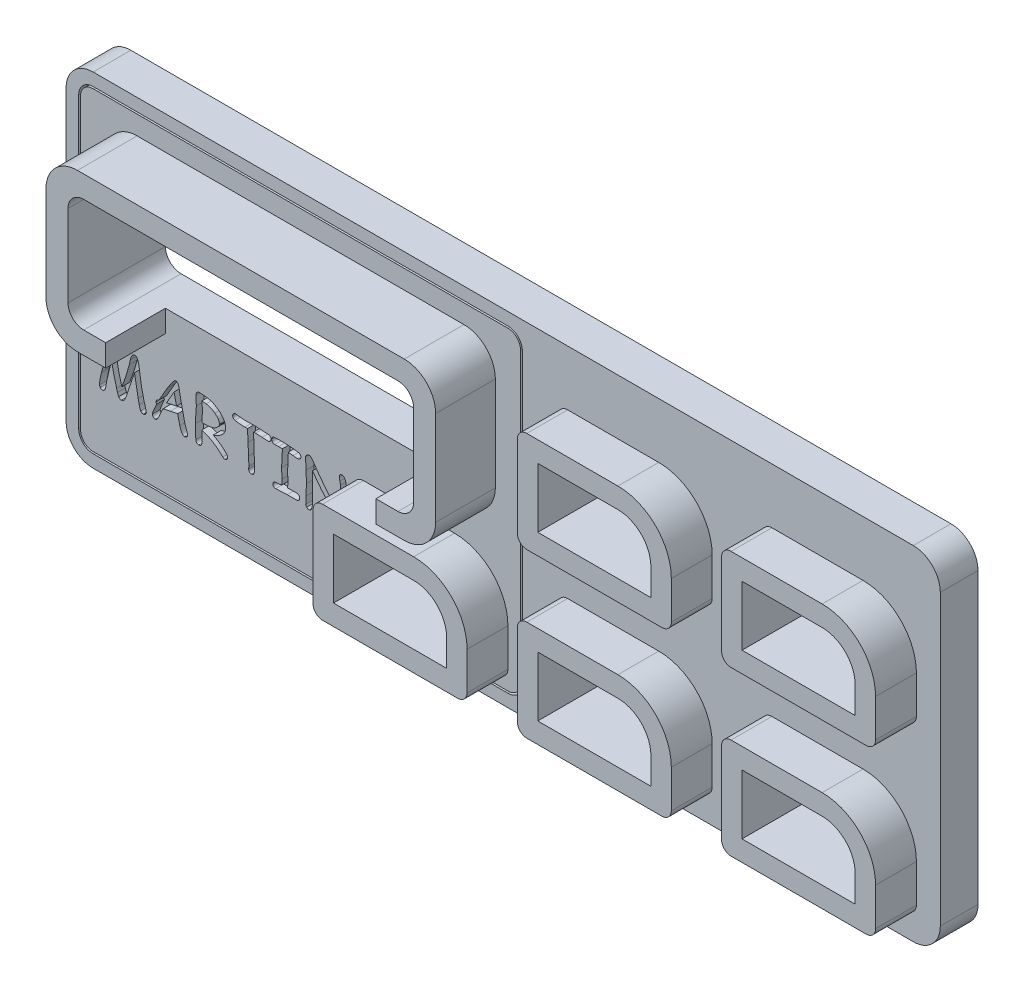
SolidWorks part; units mm, degrees
ref_plane "Plan de face" through (0, 0, 0) normal (0, 0, 1) x (1, 0, 0)
ref_plane "Plan de dessus" through (0, 0, 0) normal (0, 1, 0) x (1, 0, 0)
ref_plane "Plan de droite" through (0, 0, 0) normal (1, 0, 0) x (0, 0, -1)
sketch "Esquisse1" plane through (0, 0, 0) normal (0, 0, 1) x (1, 0, 0)
  line L1 (2, 0) -> (68, 0)
  line L2 (0, 2) -> (0, 48)
  line L3 (2, 50) -> (68, 50)
  line L4 (70, 2) -> (70, 48)
  arc A0 (68, 0) -> (70, 2) centre (68, 2) ccw
  arc A1 (0, 48) -> (2, 50) centre (2, 48) cw
  arc A2 (68, 50) -> (70, 48) centre (68, 48) cw
  arc A3 (2, 0) -> (0, 2) centre (2, 2) cw
  point P7 (70, 0)
  point P12 (70, 50)
  point P15 (0, 0)
  dimension "D3" = 2
  dimension "D1" = 70
  dimension "D2" = 50
extrude "Boss.-Extru.1" add sketch "Esquisse1" along normal blind 6
sketch "Esquisse2" plane through (0, 0, 6) normal (0, 0, 1) x (1, 0, 0)
  line L0 (35, 50) -> (35, 0) construction
  line L1 (9, 47) -> (61, 47)
  line L2 (4, 42) -> (4, 27)
  line L3 (9, 22) -> (13.5, 22)
  line L4 (66, 42) -> (66, 27)
  line L5 (68, 50) -> (2, 50) construction
  line L6 (2, 0) -> (68, 0) construction
  line L8 (7.5, 41) -> (7.5, 28)
  line L13 (10, 25.5) -> (13.5, 25.5)
  line L14 (62.5, 41) -> (62.5, 28)
  line L15 (10, 43.5) -> (60, 43.5)
  line L16 (13.5, 25.5) -> (13.5, 22)
  line L19 (56.5, 25.5) -> (56.5, 22)
  line L24 (56.5, 22) -> (61, 22)
  line L25 (56.5, 25.5) -> (60, 25.5)
  arc A0 (61, 47) -> (66, 42) centre (61, 42) cw
  arc A1 (4, 27) -> (9, 22) centre (9, 27) ccw
  arc A2 (61, 22) -> (66, 27) centre (61, 27) ccw
  arc A3 (9, 47) -> (4, 42) centre (9, 42) ccw
  arc A4 (7.5, 28) -> (10, 25.5) centre (10, 28) ccw
  arc A5 (60, 25.5) -> (62.5, 28) centre (60, 28) ccw
  arc A6 (60, 43.5) -> (62.5, 41) centre (60, 41) cw
  arc A7 (10, 43.5) -> (7.5, 41) centre (10, 41) ccw
  point P12 (66, 47)
  point P15 (4, 22)
  point P18 (66, 22)
  dimension "D4" = 5
  dimension "D6" = 3.5
  dimension "D9" = 2.5
  dimension "D1" = 62
  dimension "D2" = 25
  dimension "D3" = 3
  dimension "D5" = 3.5
  dimension "D7" = 3.5
  dimension "D8" = 3.5
  dimension "D10" = 43
extrude "Boss.-Extru.2" add sketch "Esquisse2" along normal blind 9.5
sketch "Esquisse4" plane through (0, 0, 6) normal (0, 0, 1) x (1, 0, 0)
  line L0 (2, 0) -> (68, 0) construction
  line L1 (45, 1.5) -> (66.5, 1.5)
  line L2 (43.5, 3) -> (43.5, 16)
  line L3 (45, 17.5) -> (59.5, 17.5)
  line L4 (68, 3) -> (68, 9)
  line L5 (70, 2) -> (70, 48) construction
  line L6 (46.75, 4.75) -> (46.75, 14.25)
  line L7 (46.75, 14.25) -> (59.5, 14.25)
  line L8 (64.75, 4.75) -> (64.75, 9)
  line L9 (46.75, 4.75) -> (64.75, 4.75)
  arc A0 (43.5, 16) -> (45, 17.5) centre (45, 16) cw
  arc A1 (45, 1.5) -> (43.5, 3) centre (45, 3) cw
  arc A2 (66.5, 1.5) -> (68, 3) centre (66.5, 3) ccw
  arc A3 (59.5, 17.5) -> (68, 9) centre (59.5, 9) cw
  arc A4 (46.75, 14.25) -> (46.75, 14.25) centre (46.75, 14.25) cw
  arc A5 (59.5, 14.25) -> (64.75, 9) centre (59.5, 9) cw
  arc A6 (64.75, 4.75) -> (64.75, 4.75) centre (64.75, 4.75) ccw
  arc A7 (46.75, 4.75) -> (46.75, 4.75) centre (46.75, 4.75) cw
  point P10 (43.5, 17.5)
  point P13 (43.5, 1.5)
  point P18 (68, 17.5)
  dimension "D5" = 1.5
  dimension "D6" = 8.5
  dimension "D1" = 1.5
  dimension "D2" = 2
  dimension "D3" = 24.5
  dimension "D4" = 16
  dimension "D7" = 3.25
extrude "Boss.-Extru.3" add sketch "Esquisse4" along normal blind 6.5
sketch "Esquisse5" plane through (0, 0, 6) normal (0, 0, 1) x (1, 0, 0)
  line L0 (60, 25.5) -> (56.5, 25.5) construction
  line L1 (62.5, 41) -> (62.5, 28) construction
  line L2 (10, 43.5) -> (60, 43.5) construction
  line L3 (7.5, 28) -> (7.5, 41) construction
  line L4 (46.75, 4.75) -> (64.75, 4.75)
  line L5 (64.75, 4.75) -> (64.75, 9)
  line L6 (59.5, 14.25) -> (46.75, 14.25)
  line L7 (46.75, 14.25) -> (46.75, 4.75)
  line L8 (46.75, 4.75) -> (64.75, 4.75)
  line L9 (64.75, 4.75) -> (64.75, 9)
  line L10 (59.5, 14.25) -> (46.75, 14.25)
  line L11 (46.75, 14.25) -> (46.75, 4.75)
  line L12 (60, 25.5) -> (10, 25.5)
  line L13 (62.5, 41) -> (62.5, 28)
  line L14 (10, 43.5) -> (60, 43.5)
  line L15 (7.5, 28) -> (7.5, 41)
  arc A0 (60, 25.5) -> (62.5, 28) centre (60, 28) ccw construction
  arc A1 (64.75, 9) -> (59.5, 14.25) centre (59.5, 9) ccw
  arc A2 (64.75, 9) -> (59.5, 14.25) centre (59.5, 9) ccw
  arc A3 (62.5, 41) -> (60, 43.5) centre (60, 41) ccw construction
  arc A4 (10, 43.5) -> (7.5, 41) centre (10, 41) ccw construction
  arc A5 (7.5, 28) -> (10, 25.5) centre (10, 28) ccw construction
  arc A6 (60, 25.5) -> (62.5, 28) centre (60, 28) ccw
  arc A7 (62.5, 41) -> (60, 43.5) centre (60, 41) ccw
  arc A8 (10, 43.5) -> (7.5, 41) centre (10, 41) ccw
  arc A9 (7.5, 28) -> (10, 25.5) centre (10, 28) ccw
  dimension "D1" = 0
extrude "Enlèv. mat.-Extru.1" cut sketch "Esquisse5" against normal through all
sketch "Esquisse6" plane through (0, 0, 6) normal (0, 0, 1) x (1, 0, 0)
  line L0 (2.5, 9.5) -> (43.5, 9.5) construction
  line L2 (2, 0) -> (68, 0) construction
  line L3 (0, 48) -> (0, 2) construction
  line L4 (43.5, 16) -> (43.5, 3) construction
  text T0 "MARTIN" font "Comic Sans MS" height 7
  dimension "D1" = 9.5
  dimension "D2" = 2.5
extrude "Enlèv. mat.-Extru.2" cut sketch "Esquisse6" against normal blind 1.25
sketch "Esquisse7" plane through (0, 0, 0) normal (0, 0, 1) x (1, 0, 0)
  line L0 (79.25, 4.75) -> (97.25, 4.75)
  line L4 (97.25, 4.75) -> (97.25, 9)
  line L5 (92, 14.25) -> (79.25, 14.25)
  line L6 (79.25, 14.25) -> (79.25, 4.75)
  line L7 (76, 16) -> (76, 3)
  line L13 (2, 52.3) -> (132.5, 52.3) construction
  line L14 (-2.3, 48) -> (-2.3, 2) construction
  line L15 (2, -2.3) -> (132.5, -2.3) construction
  line L16 (70.3, 2) -> (70.3, 48)
  line L17 (68, 50.3) -> (2, 50.3)
  line L18 (-0.3, 48) -> (-0.3, 2)
  line L19 (2, -0.3) -> (68, -0.3)
  line L20 (70.3, 2) -> (70.3, 48) construction
  line L21 (68, 50.3) -> (2, 50.3) construction
  line L22 (-0.3, 48) -> (-0.3, 2) construction
  line L23 (2, -0.3) -> (68, -0.3) construction
  line L24 (136.8, 48) -> (136.8, 2) construction
  line L25 (77.5, 1.5) -> (99, 1.5)
  line L26 (100.5, 3) -> (100.5, 9)
  line L27 (92, 17.5) -> (77.5, 17.5)
  line L28 (46.75, 4.75) -> (64.75, 4.75)
  line L29 (46.75, 14.25) -> (46.75, 4.75)
  line L30 (59.5, 14.25) -> (46.75, 14.25)
  line L31 (64.75, 4.75) -> (64.75, 9)
  line L32 (46.75, 4.75) -> (64.75, 4.75) construction
  line L33 (46.75, 14.25) -> (46.75, 4.75) construction
  line L34 (59.5, 14.25) -> (46.75, 14.25) construction
  line L35 (64.75, 4.75) -> (64.75, 9) construction
  line L36 (43.5, 16) -> (43.5, 3)
  line L37 (45, 1.5) -> (66.5, 1.5)
  line L38 (68, 3) -> (68, 9)
  line L39 (59.5, 17.5) -> (45, 17.5)
  line L40 (43.5, 16) -> (43.5, 3) construction
  line L41 (45, 1.5) -> (66.5, 1.5) construction
  line L42 (68, 3) -> (68, 9) construction
  line L43 (59.5, 17.5) -> (45, 17.5) construction
  line L44 (111.75, 4.75) -> (129.75, 4.75)
  line L45 (129.75, 4.75) -> (129.75, 9)
  line L46 (124.5, 14.25) -> (111.75, 14.25)
  line L47 (111.75, 14.25) -> (111.75, 4.75)
  line L48 (108.5, 16) -> (108.5, 3)
  line L49 (110, 1.5) -> (131.5, 1.5)
  line L50 (133, 3) -> (133, 9)
  line L51 (124.5, 17.5) -> (110, 17.5)
  line L52 (79.25, 30.75) -> (97.25, 30.75)
  line L53 (97.25, 30.75) -> (97.25, 35)
  line L54 (92, 40.25) -> (79.25, 40.25)
  line L55 (79.25, 40.25) -> (79.25, 30.75)
  line L56 (76, 42) -> (76, 29)
  line L57 (77.5, 27.5) -> (99, 27.5)
  line L58 (100.5, 29) -> (100.5, 35)
  line L59 (92, 43.5) -> (77.5, 43.5)
  line L60 (111.75, 30.75) -> (129.75, 30.75)
  line L61 (129.75, 30.75) -> (129.75, 35)
  line L62 (124.5, 40.25) -> (111.75, 40.25)
  line L63 (111.75, 40.25) -> (111.75, 30.75)
  line L64 (108.5, 42) -> (108.5, 29)
  line L65 (110, 27.5) -> (131.5, 27.5)
  line L66 (133, 29) -> (133, 35)
  line L67 (124.5, 43.5) -> (110, 43.5)
  line L68 (46.75, 30.75) -> (64.75, 30.75) [skipped]
  line L69 (64.75, 30.75) -> (64.75, 35) [skipped]
  line L70 (59.5, 40.25) -> (46.75, 40.25) [skipped]
  line L71 (46.75, 40.25) -> (46.75, 30.75) [skipped]
  line L72 (43.5, 42) -> (43.5, 29) [skipped]
  line L73 (45, 27.5) -> (66.5, 27.5) [skipped]
  line L74 (68, 29) -> (68, 35) [skipped]
  line L75 (59.5, 43.5) -> (45, 43.5) [skipped]
  arc A0 (97.25, 9) -> (92, 14.25) centre (92, 9) ccw
  arc A1 (77.5, 17.5) -> (76, 16) centre (77.5, 16) ccw
  arc A2 (76, 3) -> (77.5, 1.5) centre (77.5, 3) ccw
  arc A3 (99, 1.5) -> (100.5, 3) centre (99, 3) ccw
  arc A4 (132.5, 52.3) -> (136.8, 48) centre (132.5, 48) cw construction
  arc A5 (-2.3, 2) -> (2, -2.3) centre (2, 2) ccw construction
  arc A6 (132.5, -2.3) -> (136.8, 2) centre (132.5, 2) ccw construction
  arc A7 (2, 52.3) -> (-2.3, 48) centre (2, 48) ccw construction
  arc A12 (68, -0.3) -> (70.3, 2) centre (68, 2) ccw
  arc A13 (70.3, 48) -> (68, 50.3) centre (68, 48) ccw
  arc A14 (2, 50.3) -> (-0.3, 48) centre (2, 48) ccw
  arc A15 (-0.3, 2) -> (2, -0.3) centre (2, 2) ccw
  arc A16 (68, -0.3) -> (70.3, 2) centre (68, 2) ccw construction
  arc A17 (70.3, 48) -> (68, 50.3) centre (68, 48) ccw construction
  arc A18 (2, 50.3) -> (-0.3, 48) centre (2, 48) ccw construction
  arc A19 (-0.3, 2) -> (2, -0.3) centre (2, 2) ccw construction
  arc A20 (100.5, 9) -> (92, 17.5) centre (92, 9) ccw
  arc A21 (64.75, 9) -> (59.5, 14.25) centre (59.5, 9) ccw
  arc A22 (64.75, 9) -> (59.5, 14.25) centre (59.5, 9) ccw construction
  arc A23 (129.75, 9) -> (124.5, 14.25) centre (124.5, 9) ccw
  arc A24 (110, 17.5) -> (108.5, 16) centre (110, 16) ccw
  arc A25 (108.5, 3) -> (110, 1.5) centre (110, 3) ccw
  arc A26 (45, 17.5) -> (43.5, 16) centre (45, 16) ccw
  arc A27 (43.5, 3) -> (45, 1.5) centre (45, 3) ccw
  arc A28 (66.5, 1.5) -> (68, 3) centre (66.5, 3) ccw
  arc A29 (68, 9) -> (59.5, 17.5) centre (59.5, 9) ccw
  arc A30 (45, 17.5) -> (43.5, 16) centre (45, 16) ccw construction
  arc A31 (43.5, 3) -> (45, 1.5) centre (45, 3) ccw construction
  arc A32 (66.5, 1.5) -> (68, 3) centre (66.5, 3) ccw construction
  arc A33 (68, 9) -> (59.5, 17.5) centre (59.5, 9) ccw construction
  arc A34 (131.5, 1.5) -> (133, 3) centre (131.5, 3) ccw
  arc A35 (133, 9) -> (124.5, 17.5) centre (124.5, 9) ccw
  arc A36 (97.25, 35) -> (92, 40.25) centre (92, 35) ccw
  arc A37 (77.5, 43.5) -> (76, 42) centre (77.5, 42) ccw
  arc A38 (76, 29) -> (77.5, 27.5) centre (77.5, 29) ccw
  arc A39 (99, 27.5) -> (100.5, 29) centre (99, 29) ccw
  arc A40 (100.5, 35) -> (92, 43.5) centre (92, 35) ccw
  arc A41 (129.75, 35) -> (124.5, 40.25) centre (124.5, 35) ccw
  arc A42 (110, 43.5) -> (108.5, 42) centre (110, 42) ccw
  arc A43 (108.5, 29) -> (110, 27.5) centre (110, 29) ccw
  arc A44 (131.5, 27.5) -> (133, 29) centre (131.5, 29) ccw
  arc A45 (133, 35) -> (124.5, 43.5) centre (124.5, 35) ccw
  arc A46 (64.75, 35) -> (59.5, 40.25) centre (59.5, 35) ccw [skipped]
  arc A47 (45, 43.5) -> (43.5, 42) centre (45, 42) ccw [skipped]
  arc A48 (43.5, 29) -> (45, 27.5) centre (45, 29) ccw [skipped]
  arc A49 (66.5, 27.5) -> (68, 29) centre (66.5, 29) ccw [skipped]
  arc A50 (68, 35) -> (59.5, 43.5) centre (59.5, 35) ccw [skipped]
  dimension "D3" = 2
  dimension "D9" = 8
  dimension "D10" = 10
  dimension "D11" = 2
  dimension "D12" = 3.8
  dimension "D1" = 0.3
  dimension "D5" = 0
  dimension "D6" = 0
  dimension "D7" = 3
  dimension "D8" = 2
extrude "Boss.-Extru.4" add sketch "Esquisse7" along normal up to surface (12.5 mm away) separate body contours L26 A20 L27 A1 L7 A2 L25 A3 A0 L4 L0 L6 L5 | L58 A40 L59 A37 L56 A38 L57 A39 A36 L53 L52 L55 L54 | L66 A45 L67 A42 L64 A43 L65 A44 A41 L61 L60 L63 L62 | L50 A35 L51 A24 L48 A25 L49 A34 A23 L45 L44 L47 L46 up to face at (55.0562, 8.8062, 12.5)
sketch "Esquisse8" plane through (0, 0, 0) normal (0, 0, 1) x (1, 0, 0)
  line L0 (136.8, 48) -> (136.8, 2) construction
  line L1 (2, -2.3) -> (132.5, -2.3) construction
  line L2 (-2.3, 48) -> (-2.3, 2) construction
  line L3 (2, 52.3) -> (132.5, 52.3) construction
  line L4 (136.8, 48) -> (136.8, 2)
  line L5 (2, -2.3) -> (132.5, -2.3)
  line L6 (-2.3, 48) -> (-2.3, 2)
  line L7 (2, 52.3) -> (132.5, 52.3)
  line L8 (68, 50.3) -> (2, 50.3) construction
  line L9 (-0.3, 48) -> (-0.3, 2) construction
  line L10 (2, -0.3) -> (68, -0.3) construction
  line L11 (70.3, 2) -> (70.3, 48) construction
  line L12 (68, 50.3) -> (2, 50.3)
  line L13 (-0.3, 48) -> (-0.3, 2)
  line L14 (2, -0.3) -> (68, -0.3)
  line L15 (70.3, 2) -> (70.3, 48)
  line L16 (97.25, 9) -> (97.25, 4.75) construction
  line L17 (97.25, 4.75) -> (79.25, 4.75) construction
  line L18 (79.25, 4.75) -> (79.25, 14.25) construction
  line L19 (79.25, 14.25) -> (92, 14.25) construction
  line L20 (97.25, 9) -> (97.25, 4.75)
  line L21 (97.25, 4.75) -> (79.25, 4.75)
  line L22 (79.25, 4.75) -> (79.25, 14.25)
  line L23 (79.25, 14.25) -> (92, 14.25)
  line L24 (111.75, 14.25) -> (124.5, 14.25)
  line L25 (111.75, 4.75) -> (111.75, 14.25)
  line L26 (129.75, 4.75) -> (111.75, 4.75)
  line L27 (129.75, 9) -> (129.75, 4.75)
  line L28 (111.75, 40.25) -> (124.5, 40.25)
  line L29 (111.75, 30.75) -> (111.75, 40.25)
  line L30 (129.75, 30.75) -> (111.75, 30.75)
  line L31 (129.75, 35) -> (129.75, 30.75)
  line L32 (79.25, 40.25) -> (92, 40.25)
  line L33 (79.25, 30.75) -> (79.25, 40.25)
  line L34 (97.25, 30.75) -> (79.25, 30.75)
  line L35 (97.25, 35) -> (97.25, 30.75)
  arc A0 (136.8, 48) -> (132.5, 52.3) centre (132.5, 48) ccw construction
  arc A1 (132.5, -2.3) -> (136.8, 2) centre (132.5, 2) ccw construction
  arc A2 (-2.3, 2) -> (2, -2.3) centre (2, 2) ccw construction
  arc A3 (2, 52.3) -> (-2.3, 48) centre (2, 48) ccw construction
  arc A4 (136.8, 48) -> (132.5, 52.3) centre (132.5, 48) ccw
  arc A5 (132.5, -2.3) -> (136.8, 2) centre (132.5, 2) ccw
  arc A6 (-2.3, 2) -> (2, -2.3) centre (2, 2) ccw
  arc A7 (2, 52.3) -> (-2.3, 48) centre (2, 48) ccw
  arc A8 (70.3, 48) -> (68, 50.3) centre (68, 48) ccw construction
  arc A9 (2, 50.3) -> (-0.3, 48) centre (2, 48) ccw construction
  arc A10 (-0.3, 2) -> (2, -0.3) centre (2, 2) ccw construction
  arc A11 (68, -0.3) -> (70.3, 2) centre (68, 2) ccw construction
  arc A12 (70.3, 48) -> (68, 50.3) centre (68, 48) ccw
  arc A13 (2, 50.3) -> (-0.3, 48) centre (2, 48) ccw
  arc A14 (-0.3, 2) -> (2, -0.3) centre (2, 2) ccw
  arc A15 (68, -0.3) -> (70.3, 2) centre (68, 2) ccw
  arc A16 (97.25, 9) -> (92, 14.25) centre (92, 9) ccw construction
  arc A17 (97.25, 9) -> (92, 14.25) centre (92, 9) ccw
  arc A18 (129.75, 9) -> (124.5, 14.25) centre (124.5, 9) ccw
  arc A19 (129.75, 35) -> (124.5, 40.25) centre (124.5, 35) ccw
  arc A20 (97.25, 35) -> (92, 40.25) centre (92, 35) ccw
  dimension "D3" = 16.5
  dimension "D4" = 14.5
  dimension "D1" = 2
  dimension "D2" = 2
extrude "Boss.-Extru.5" add sketch "Esquisse8" along normal up to surface (6 mm away) up to face at (20.4973, 12.4894, 6)
